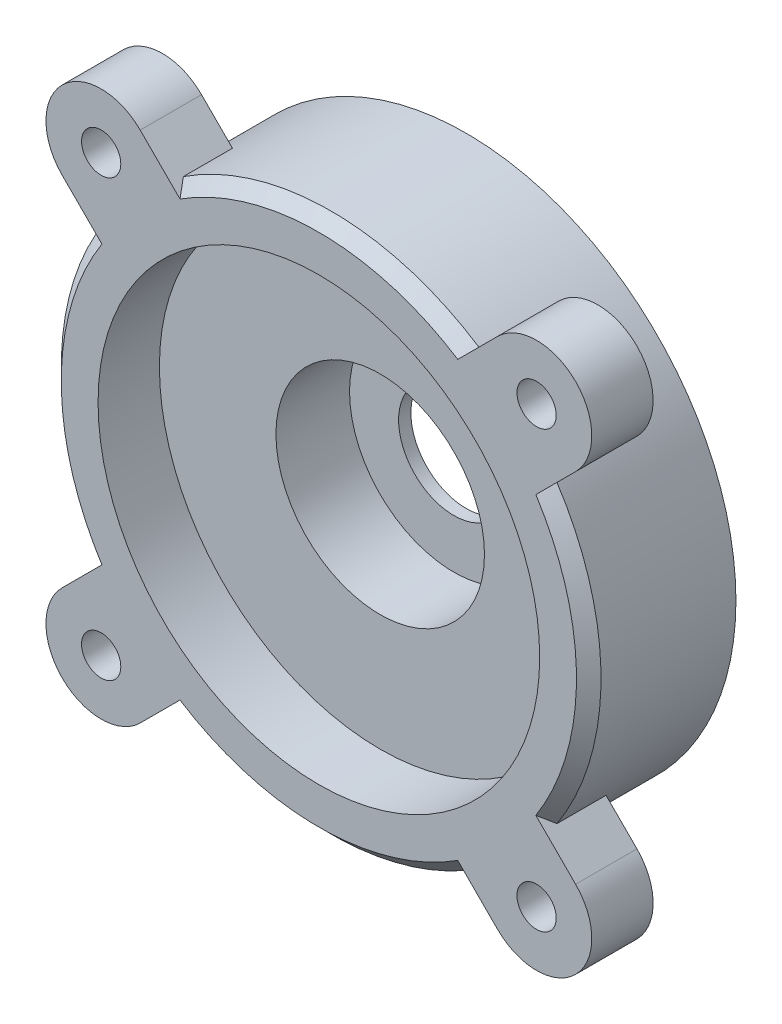
SolidWorks part; units mm, degrees
ref_plane "Front Plane" through (0, 0, 0) normal (0, 0, 1) x (1, 0, 0)
ref_plane "Top Plane" through (0, 0, 0) normal (0, 1, 0) x (1, 0, 0)
ref_plane "Right Plane" through (0, 0, 0) normal (1, 0, 0) x (0, 0, -1)
sketch "Sketch1" plane through (0, 0, 0) normal (0, 0, 1) x (1, 0, 0)
  circle A0 centre (0, 0) radius 22
  dimension "D1" = 44
extrude "Boss-Extrude1" add sketch "Sketch1" along normal mid plane 12
chamfer "Chamfer1" distance 1 angle 45 1 edges at (22, 0, 6)
sketch "Sketch8" plane through (0, 0, 6) normal (0, 0, 1) x (1, 0, 0)
  line L17 (20.9304, -14.5664) -> (17.6863, -11.3223)
  line L19 (14.5664, 20.9304) -> (11.3223, 17.6863)
  line L20 (20.9304, 14.5664) -> (17.6863, 11.3223)
  line L21 (17.6863, 11.3223) -> (11.3223, 17.6863)
  line L22 (14.5664, -20.9304) -> (11.3223, -17.6863)
  line L23 (11.3223, -17.6863) -> (17.6863, -11.3223)
  line L24 (-14.5664, -20.9304) -> (-11.3223, -17.6863)
  line L25 (-20.9304, -14.5664) -> (-17.6863, -11.3223)
  line L26 (-17.6863, -11.3223) -> (-11.3223, -17.6863)
  line L27 (-20.9304, 14.5664) -> (-17.6863, 11.3223)
  line L28 (-14.5664, 20.9304) -> (-11.3223, 17.6863)
  line L29 (-11.3223, 17.6863) -> (-17.6863, 11.3223)
  circle A2 centre (17.7484, 17.7484) radius 1.6
  circle A12 centre (0, 0) radius 21 construction
  arc A14 (14.5664, 20.9304) -> (20.9304, 14.5664) centre (17.7484, 17.7484) cw
  circle A15 centre (17.7484, -17.7484) radius 1.6
  arc A16 (20.9304, -14.5664) -> (14.5664, -20.9304) centre (17.7484, -17.7484) cw
  circle A17 centre (-17.7484, -17.7484) radius 1.6
  arc A18 (-14.5664, -20.9304) -> (-20.9304, -14.5664) centre (-17.7484, -17.7484) cw
  circle A19 centre (-17.7484, 17.7484) radius 1.6
  arc A20 (-20.9304, 14.5664) -> (-14.5664, 20.9304) centre (-17.7484, 17.7484) cw
  point P6 (17.7484, 17.7484)
  point P9 (0, 0)
  point P19 (17.7484, -17.7484)
  point P27 (-17.7484, -17.7484)
  point P31 (0, 0)
  point P36 (-17.7484, 17.7484)
  point P40 (0, 0)
  dimension "D1" = 4
extrude "Boss-Extrude2" add sketch "Sketch8" against normal blind 5
sketch "Sketch9" plane through (0, 0, 6) normal (0, 0, 1) x (1, 0, 0)
  circle A0 centre (0, 0) radius 18
extrude "Cut-Extrude1" cut sketch "Sketch9" against normal blind 5
sketch "Sketch10" plane through (0, 0, 1) normal (0, 0, 1) x (1, 0, 0)
  circle A0 centre (0, 0) radius 8.5
extrude "Cut-Extrude2" cut sketch "Sketch10" against normal blind 6
sketch "Sketch11" plane through (0, 0, -5) normal (0, 0, 1) x (1, 0, 0)
  circle A0 centre (0, 0) radius 4.5
extrude "Cut-Extrude3" cut sketch "Sketch11" against normal blind 1
